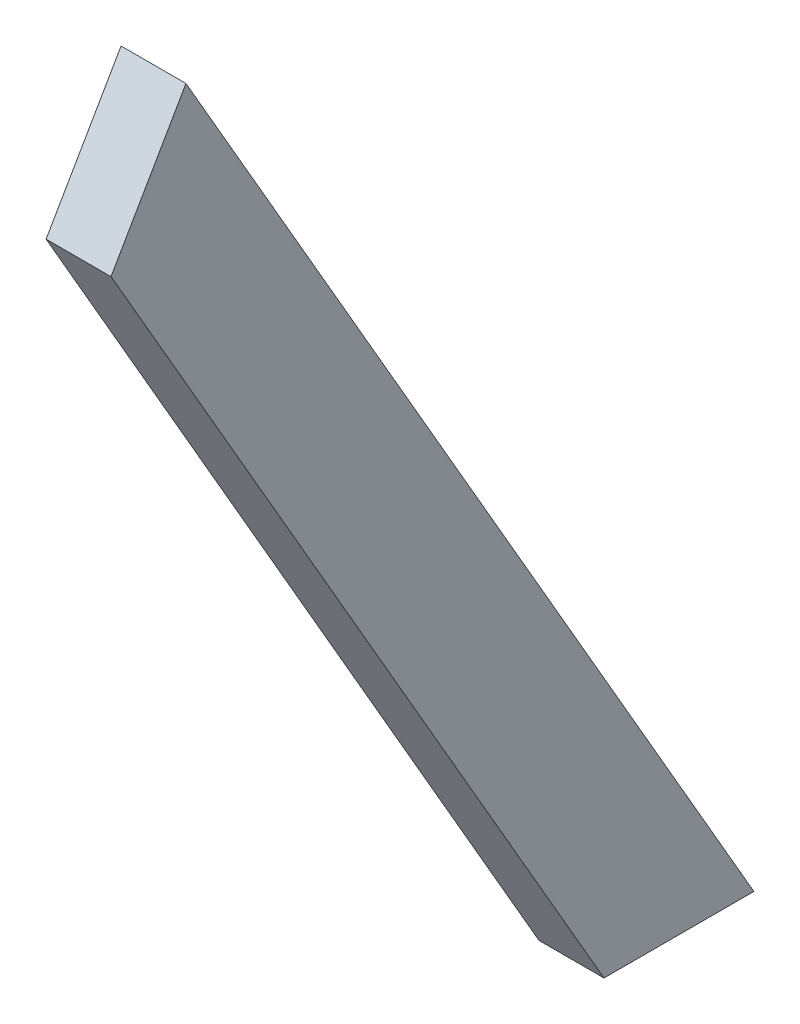
SolidWorks part; units mm, degrees
ref_plane "Front Plane" through (0, 0, 0) normal (0, 0, 1) x (1, 0, 0)
ref_plane "Top Plane" through (0, 0, 0) normal (0, 1, 0) x (1, 0, 0)
ref_plane "Right Plane" through (0, 0, 0) normal (1, 0, 0) x (0, 0, -1)
sketch "Sketch2" plane through (0, 0, 0) normal (1, 0, 0) x (0, 0, -1)
  line L0 (0, 0) -> (-192.9206, 334.1483)
  line L1 (-192.9206, 334.1483) -> (-163.5912, 384.9483)
  line L2 (-163.5912, 384.9483) -> (58.6588, 0)
  line L3 (58.6588, 0) -> (0, 0)
  line L4 (0, 0) -> (43.9941, 25.4) construction
  line L5 (0, 0) -> (-8.7538, 0) construction
  line L6 (-163.5912, 384.9483) -> (-167.8456, 377.5795) construction
  point P8 (49.8588, 15.242)
  dimension "D1" = 50.8
  dimension "D2" = 444.5
  dimension "D3" = 60
  dimension "D4" = 60
extrude "Boss-Extrude1" add sketch "Sketch2" along normal blind 25.4
